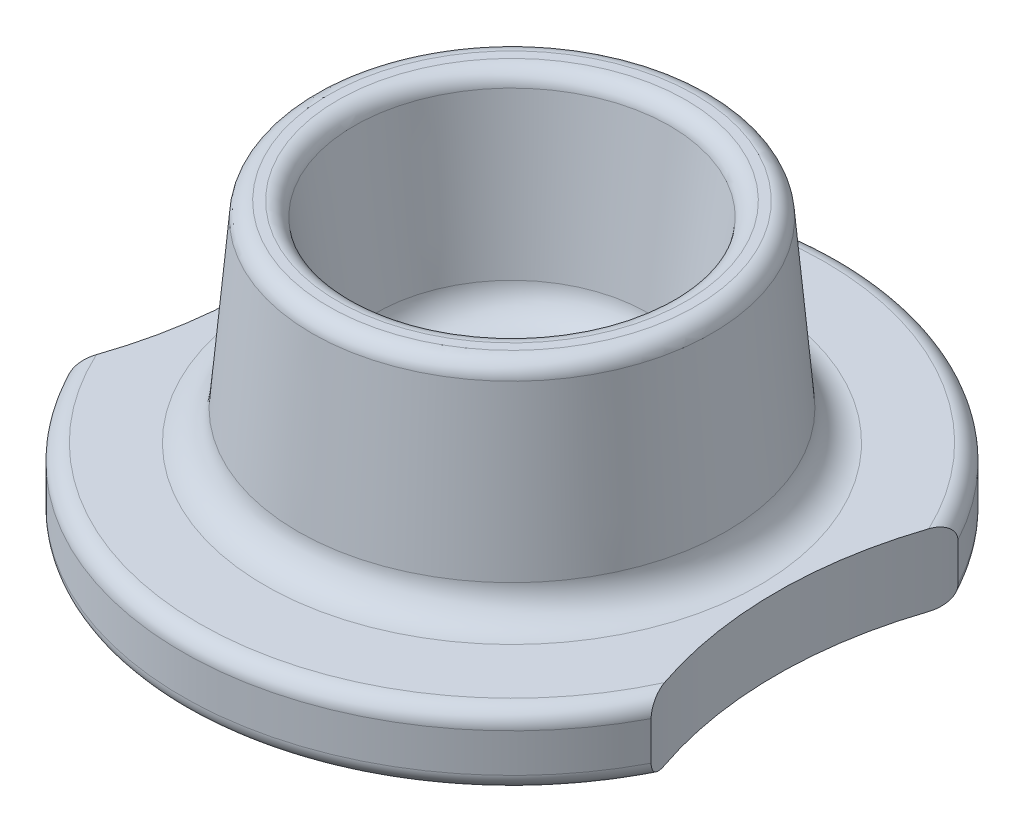
SolidWorks part; units mm, degrees
ref_plane "Plano frontal" through (0, 0, 0) normal (0, 0, 1) x (1, 0, 0)
ref_plane "Plano superior" through (0, 0, 0) normal (0, 1, 0) x (1, 0, 0)
ref_plane "Plano direito" through (0, 0, 0) normal (1, 0, 0) x (0, 0, -1)
sketch "Esboço1" plane through (0, 0, 0) normal (0, 0, 1) x (1, 0, 0)
  line L0 (17.3834, 40.7659) -> (17.3834, -37.8053) construction
  line L1 (46.3834, 40.7659) -> (53.3834, 40.7659)
  line L2 (53.3834, 40.7659) -> (56.7034, 2.7659)
  line L3 (56.7034, 2.7659) -> (77.1334, 2.7659)
  line L4 (77.1334, 2.7659) -> (77.1334, -10.2341)
  line L5 (48.1334, -28.9341) -> (49.7834, -10.2341)
  line L6 (49.7834, -10.2341) -> (77.1334, -10.2341)
  line L7 (48.1334, -28.9341) -> (40.8834, -28.9341)
  line L8 (40.8834, -28.9341) -> (38.437, -0.9341)
  line L9 (38.437, -0.9341) -> (17.3834, -0.9341)
  line L10 (46.3834, 40.7659) -> (41.2034, 5.7659)
  line L11 (41.2034, 5.7659) -> (17.3834, 5.7659)
  line L12 (17.3834, -0.9341) -> (17.3834, 5.7659)
  dimension "D1" = 23.82
  dimension "D2" = 29
  dimension "D3" = 36
  dimension "D4" = 39.32
  dimension "D5" = 59.75
  dimension "D6" = 30.75
  dimension "D7" = 32.4
  dimension "D8" = 23.5
  dimension "D9" = 28
  dimension "D10" = 38
  dimension "D11" = 13
  dimension "D12" = 35
  dimension "D13" = 6.7
revolve "Revolução1" add sketch "Esboço1" angle 360 about L0
fillet "Filete1" radius 6 1 edges at (17.3834, 5.7659, 23.82)
fillet "Filete2" radius 6 1 edges at (17.3834, -0.9341, 21.0537)
fillet "Filete3" radius 3 1 edges at (17.3834, -10.2341, 32.4)
fillet "Filete4" radius 3 1 edges at (17.3834, -10.2341, 59.75)
fillet "Filete5" radius 3 1 edges at (17.3834, 2.7659, 59.75)
fillet "Filete6" radius 3 1 edges at (17.3834, 40.7659, 36)
fillet "Filete7" radius 3 1 edges at (17.3834, 40.7659, 29)
fillet "Filete8" radius 6 1 edges at (17.3834, 2.7659, 39.32)
fillet "Filete9" radius 2 2 edges at (17.3834, -28.9341, 23.5) (17.3834, -28.9341, 30.75)
sketch "Esboço2" plane through (0, -10.2341, 0) normal (0, -1, 0) x (1, 0, 0)
  line L0 (77.1334, 0) -> (17.3834, 0) construction
  line L1 (17.3834, 0) -> (17.3834, -70.7111) construction
  line L2 (73.2274, -20.75) -> (73.2274, 20.75) construction
  circle A0 centre (17.3834, 0) radius 59.75 construction
  circle A1 centre (139.8132, -0.5061) radius 75
  circle A2 centre (-105.0465, -0.5061) radius 75
  dimension "D1" = 150
  dimension "D2" = 41.5
extrude "Corte-extrusão3" cut sketch "Esboço2" against normal through all contours A2 | A1
